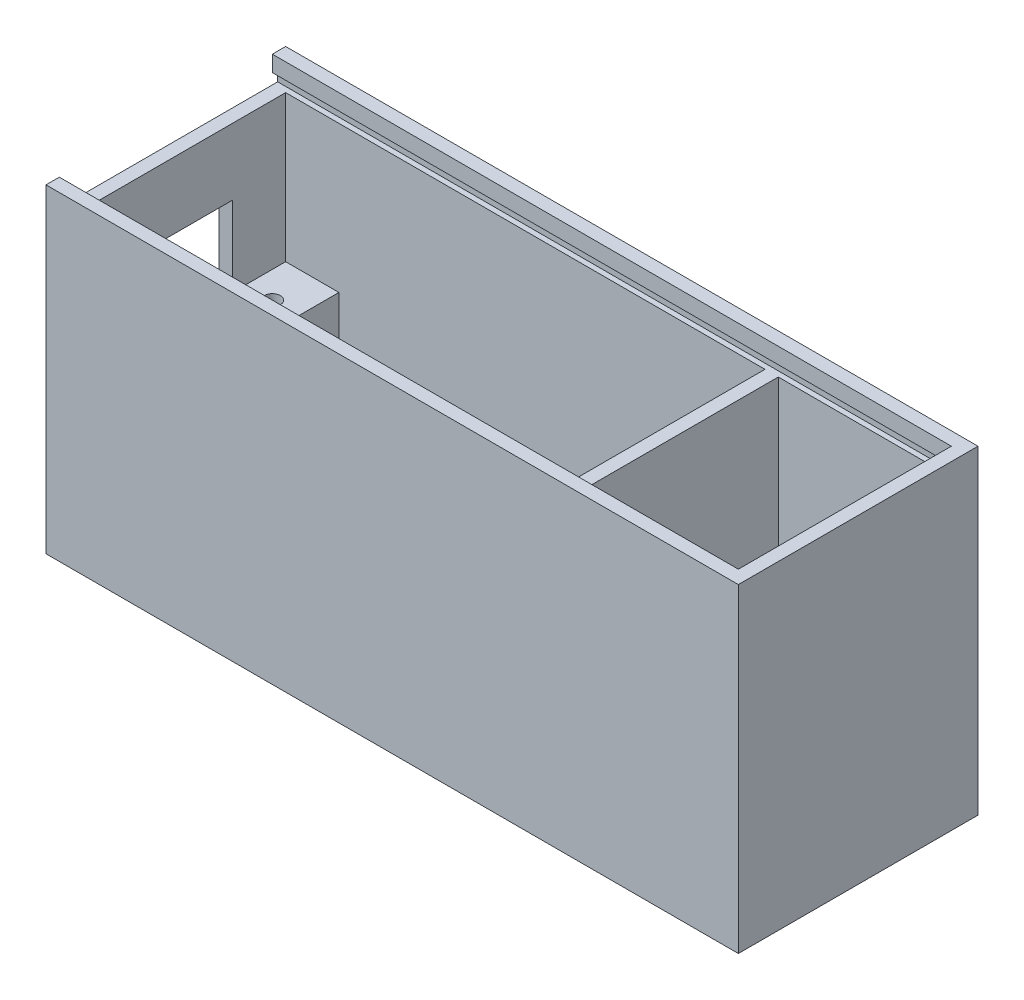
SolidWorks part; units mm, degrees
ref_plane "Front Plane" through (0, 0, 0) normal (0, 0, 1) x (1, 0, 0)
ref_plane "Top Plane" through (0, 0, 0) normal (0, 1, 0) x (1, 0, 0)
ref_plane "Right Plane" through (0, 0, 0) normal (1, 0, 0) x (0, 0, -1)
sketch "Sketch1" plane through (0, 0, 0) normal (0, 1, 0) x (1, 0, 0)
  line L1 (-65, -22.5) -> (65, -22.5)
  line L2 (-65, -22.5) -> (-65, 22.5)
  line L3 (-65, 22.5) -> (65, 22.5)
  line L4 (65, -22.5) -> (65, 22.5)
  line L5 (-65, -22.5) -> (65, 22.5) construction
  line L6 (-65, 22.5) -> (65, -22.5) construction
  point P0 (0, 0)
extrude "Boss-Extrude1" add sketch "Sketch1" along normal blind 60
shell "Shell3" thickness 2.5
sketch "Sketch3" plane through (0, 2.5, 0) normal (0, 1, 0) x (1, 0, 0)
  line L0 (-62.5, 20) -> (27.5, 20)
  line L1 (62.5, 20) -> (-62.5, 20) construction
sketch "Sketch4" plane through (0, 2.5, 0) normal (0, 1, 0) x (1, 0, 0)
  line L0 (-62.5, -20) -> (62.5, -20) construction
  line L1 (27.5, 20) -> (30, 20)
  line L2 (27.5, 20) -> (27.5, -20)
  line L3 (27.5, -20) -> (30, -20)
  line L4 (30, 20) -> (30, -20)
extrude "Boss-Extrude2" add sketch "Sketch4" along normal blind 57.5
sketch "Sketch5" plane through (0, 2.5, 0) normal (0, 1, 0) x (1, 0, 0)
  line L0 (30, -20) -> (62.5, -20) construction
  line L1 (62.5, 20) -> (49.5, 20)
  line L2 (62.5, 20) -> (62.5, -20)
  line L3 (62.5, -20) -> (49.5, -20)
  line L4 (49.5, 20) -> (49.5, -20)
extrude "Boss-Extrude3" add sketch "Sketch5" along normal blind 35
sketch "Sketch6" plane through (0, 2.5, 0) normal (0, 1, 0) x (1, 0, 0)
  line L0 (-62.5, -20) -> (27.5, -20) construction
  line L1 (27.5, 20) -> (7.5, 20)
  line L2 (27.5, 20) -> (27.5, -20)
  line L3 (27.5, -20) -> (7.5, -20)
  line L4 (7.5, 20) -> (7.5, -20)
extrude "Boss-Extrude4" add sketch "Sketch6" along normal blind 20
sketch "Sketch7" plane through (0, 2.5, 0) normal (0, 1, 0) x (1, 0, 0)
  line L0 (-62.5, -20) -> (7.5, -20) construction
  line L1 (-62.5, 20) -> (-52.5, 20)
  line L2 (-62.5, 20) -> (-62.5, -20)
  line L3 (-62.5, -20) -> (-52.5, -20)
  line L4 (-52.5, 20) -> (-52.5, -20)
extrude "Boss-Extrude5" add sketch "Sketch7" along normal blind 25
sketch "Sketch8" plane through (0, 27.5, 0) normal (0, 1, 0) x (1, 0, 0)
  line L0 (-62.5, 20) -> (-52.5, -20)
  line L1 (-52.5, 20) -> (-62.5, -20)
  line L2 (-57.5, 12.5) -> (-57.5, -12.5)
  circle A0 centre (-57.5, 0) radius 12.5
  point P10 (-57.5, 12.5)
  point P11 (-57.5, -12.5)
sketch "Sketch9" plane through (0, 27.5, 0) normal (0, 1, 0) x (1, 0, 0)
  circle A0 centre (-57.5, 12.5) radius 1.5
  circle A1 centre (-57.5, -12.5) radius 1.5
sketch "Sketch10" plane through (0, 37.5, 0) normal (0, 1, 0) x (1, 0, 0)
  line L0 (62.5, 20) -> (49.5, -20)
  line L1 (62.5, -20) -> (49.5, 20)
  line L2 (56, 7.5) -> (56, -7.5)
  circle A0 centre (56, 0) radius 7.5
  point P10 (56, 7.5)
  point P11 (56, -7.5)
sketch "Sketch11" plane through (0, 37.5, 0) normal (0, 1, 0) x (1, 0, 0)
  circle A0 centre (56, 7.5) radius 1.5
  circle A1 centre (56, -7.5) radius 1.5
sketch "Sketch14" plane through (-62.5, 0, 0) normal (1, 0, 0) x (0, 0, -1)
  line L0 (20, 27.5) -> (-20, 27.5) construction
  circle A0 centre (0, 27.5) radius 10
  point P4 (10, 27.5)
  point P5 (-10, 27.5)
sketch "Sketch16" plane through (-62.5, 0, 0) normal (1, 0, 0) x (0, 0, -1)
  line L1 (10, 27.5) -> (-10, 27.5)
  line L2 (10, 27.5) -> (10, 42.5)
  line L3 (10, 42.5) -> (-10, 42.5)
  line L4 (-10, 27.5) -> (-10, 42.5)
sketch "Sketch17" plane through (7.5, 0, 0) normal (-1, 0, 0) x (0, 0, 1)
  line L0 (-20, 2.5) -> (20, 2.5) construction
  circle A0 centre (0, 2.5) radius 7.5
  point P4 (-7.5, 2.5)
  point P5 (7.5, 2.5)
sketch "Sketch18" plane through (7.5, 0, 0) normal (-1, 0, 0) x (0, 0, 1)
  line L1 (-7.5, 2.5) -> (7.5, 2.5)
  line L2 (-7.5, 2.5) -> (-7.5, 12.5)
  line L3 (-7.5, 12.5) -> (7.5, 12.5)
  line L4 (7.5, 2.5) -> (7.5, 12.5)
sketch "Sketch19" plane through (-62.5, 0, 0) normal (1, 0, 0) x (0, 0, -1)
  line L0 (-20, 60) -> (-20, 27.5) construction
  line L1 (20, 60) -> (-20, 60)
  line L2 (20, 60) -> (20, 55)
  line L3 (20, 55) -> (-20, 55)
  line L4 (-20, 60) -> (-20, 55)
sketch "Sketch20" plane through (27.5, 0, 0) normal (-1, 0, 0) x (0, 0, 1)
  line L0 (20, 60) -> (20, 22.5) construction
  line L1 (-20, 60) -> (20, 60)
  line L2 (-20, 60) -> (-20, 55)
  line L3 (-20, 55) -> (20, 55)
  line L4 (20, 60) -> (20, 55)
extrude "Cut-Extrude1" cut sketch "Sketch9" against normal blind 27.5
extrude "Cut-Extrude2" cut sketch "Sketch11" against normal blind 37.5
extrude "Cut-Extrude3" cut sketch "Sketch16" against normal blind 2.5
extrude "Cut-Extrude4" cut sketch "Sketch18" against normal blind 22.5
extrude "Cut-Extrude5" cut sketch "Sketch19" against normal blind 2.5
extrude "Cut-Extrude6" cut sketch "Sketch20" against normal blind 2.5
sketch "Sketch21" plane through (0, 0, 0) normal (0, -1, 0) x (1, 0, 0)
  circle A0 centre (56, -7.5) radius 3
  circle A1 centre (56, 7.5) radius 3
  circle A2 centre (-57.5, -12.5) radius 3
  circle A3 centre (-57.5, 12.5) radius 3
extrude "Cut-Extrude7" cut sketch "Sketch21" against normal blind 5
sketch "Sketch22" plane through (0, 0, -20) normal (0, 0, 1) x (1, 0, 0)
  line L0 (62.5, 60) -> (62.5, 37.5) construction
  line L1 (-65, 55) -> (62.5, 55)
  line L2 (-65, 55) -> (-65, 57)
  line L3 (-65, 57) -> (62.5, 57)
  line L4 (62.5, 55) -> (62.5, 57)
sketch "Sketch23" plane through (0, 0, 20) normal (0, 0, -1) x (-1, 0, 0)
  line L0 (-62.5, 60) -> (-62.5, 37.5) construction
  line L1 (65, 55) -> (-62.5, 55)
  line L2 (65, 55) -> (65, 57)
  line L3 (65, 57) -> (-62.5, 57)
  line L4 (-62.5, 55) -> (-62.5, 57)
extrude "Cut-Extrude8" cut sketch "Sketch22" against normal blind 1
extrude "Cut-Extrude9" cut sketch "Sketch23" against normal blind 1
